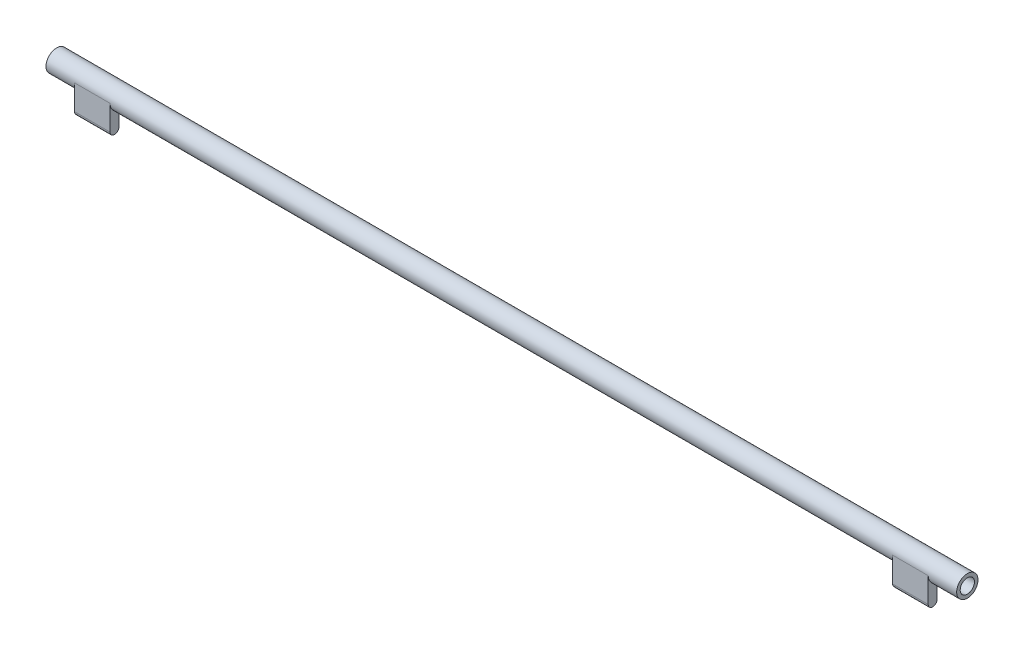
SolidWorks part; units mm, degrees
material "6061 合金"
ref_plane "前基準面" through (0, 0, 0) normal (0, 0, 1) x (1, 0, 0)
ref_plane "上基準面" through (0, 0, 0) normal (0, 1, 0) x (1, 0, 0)
ref_plane "右基準面" through (0, 0, 0) normal (1, 0, 0) x (0, 0, -1)
sketch "草圖1" plane through (0, 0, 0) normal (1, 0, 0) x (0, 0, -1)
  circle A0 centre (0, 0) radius 3
  circle A1 centre (0, 0) radius 2
  dimension "D1" = 6
  dimension "D2" = 4
extrude "填料-伸長1" add sketch "草圖1" along normal mid plane 256 contours A0
ref_plane "平面1" through (110, 0, 0) normal (1, 0, 0) x (0, 0, -1)
sketch "草圖2" plane through (110, 0, 0) normal (1, 0, 0) x (0, 0, -1)
  line L0 (-3, 0) -> (-3, -7)
  line L3 (-0.5, -2.958) -> (-0.5, -7)
  circle A0 centre (0, 0) radius 3 construction
  arc A1 (-3, 0) -> (-0.5, -2.958) centre (0, 0) ccw
  arc A2 (-3, -7) -> (-0.5, -7) centre (-1.75, -7) ccw
  dimension "D1" = 2.5
  dimension "D4" = 7
extrude "填料-伸長2" add sketch "草圖2" along normal blind 10
mirror "鏡射1" about plane through (0, 0, 0) normal (1, 0, 0) of "填料-伸長2"
